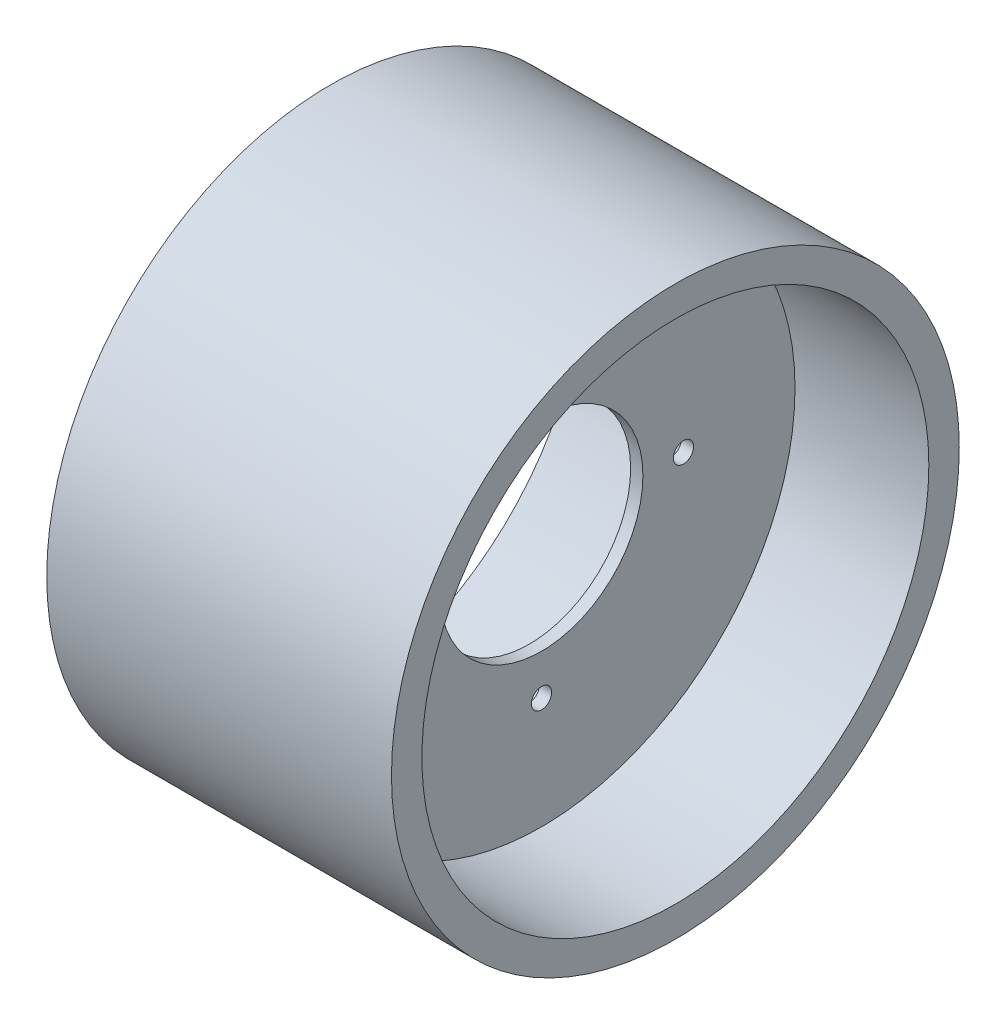
SolidWorks part; units mm, degrees
ref_plane "Front Plane" through (0, 0, 0) normal (0, 0, 1) x (1, 0, 0)
ref_plane "Top Plane" through (0, 0, 0) normal (0, 1, 0) x (1, 0, 0)
ref_plane "Right Plane" through (0, 0, 0) normal (1, 0, 0) x (0, 0, -1)
sketch "Sketch1" plane through (0, 0, 0) normal (0, 0, 1) x (1, 0, 0)
  line L0 (0, 0) -> (-54.5889, 0) construction
  line L1 (-54.5889, 0) -> (53.2667, 0) construction
  line L2 (53.2667, 0) -> (53.2667, 48.8278) construction
  line L3 (53.2667, 48.8278) -> (53.2667, -38.0611) construction
  line L4 (-54.5889, 0) -> (-54.5889, 48.8278) construction
  line L5 (-54.5889, 48.8278) -> (-54.5889, -38.0611) construction
  line L6 (-31.3556, 48.8278) -> (-14.3556, 48.8278)
  line L7 (-14.3556, 48.8278) -> (-14.3556, 47.3278)
  line L8 (-14.3556, 47.3278) -> (-20.9556, 47.3278)
  line L9 (-20.9556, 47.3278) -> (-20.9556, 39.8278)
  line L10 (-31.3556, 48.8278) -> (-31.3556, 47.3278)
  line L11 (-20.9556, 39.8278) -> (-21.5605, 39.8278)
  line L12 (-21.5605, 39.8278) -> (-21.5605, 45.4649)
  line L13 (-31.3556, 47.3278) -> (-22.4392, 47.3278)
  line L14 (-22.4392, 47.3278) -> (-22.4392, 45.4649)
  line L15 (-22.4392, 45.4649) -> (-21.5605, 45.4649)
  line L16 (-14.3556, 48.8278) -> (-14.3556, 34.8278) construction
  line L17 (-14.3556, 34.8278) -> (-31.3556, 34.8278)
  dimension "D1" = 17
  dimension "D2" = 1.5
  dimension "D4" = 6.6
  dimension "D5" = 14
  dimension "D6" = 48.8278
  dimension "D7" = 5
revolve "Revolve1" add sketch "Sketch1" angle 360 about L17
scale "Scale1" scale about centroid uniform scaling yes scale factor 10
sketch "Sketch4" plane through (-11.7127, 0, 0) normal (-1, 0, 0) x (0, 0, 1)
  line L0 (0, 34.8278) -> (70, 34.8278) construction
  line L1 (0, 34.8278) -> (0, 104.8278) construction
  line L2 (0, 34.8278) -> (0, -35.1722) construction
  line L3 (0, 34.8278) -> (-70, 34.8278) construction
  circle A0 centre (-70, 34.8278) radius 5
  circle A1 centre (0, 104.8278) radius 5
  circle A2 centre (70, 34.8278) radius 5
  circle A3 centre (0, -35.1722) radius 5
  dimension "D5" = 10
  dimension "D6" = 10
  dimension "D7" = 10
  dimension "D8" = 10
  dimension "D1" = 70
  dimension "D2" = 70
  dimension "D3" = 70
  dimension "D4" = 70
extrude "Cut-Extrude1" cut sketch "Sketch4" against normal blind 10 and the other way blind 10
